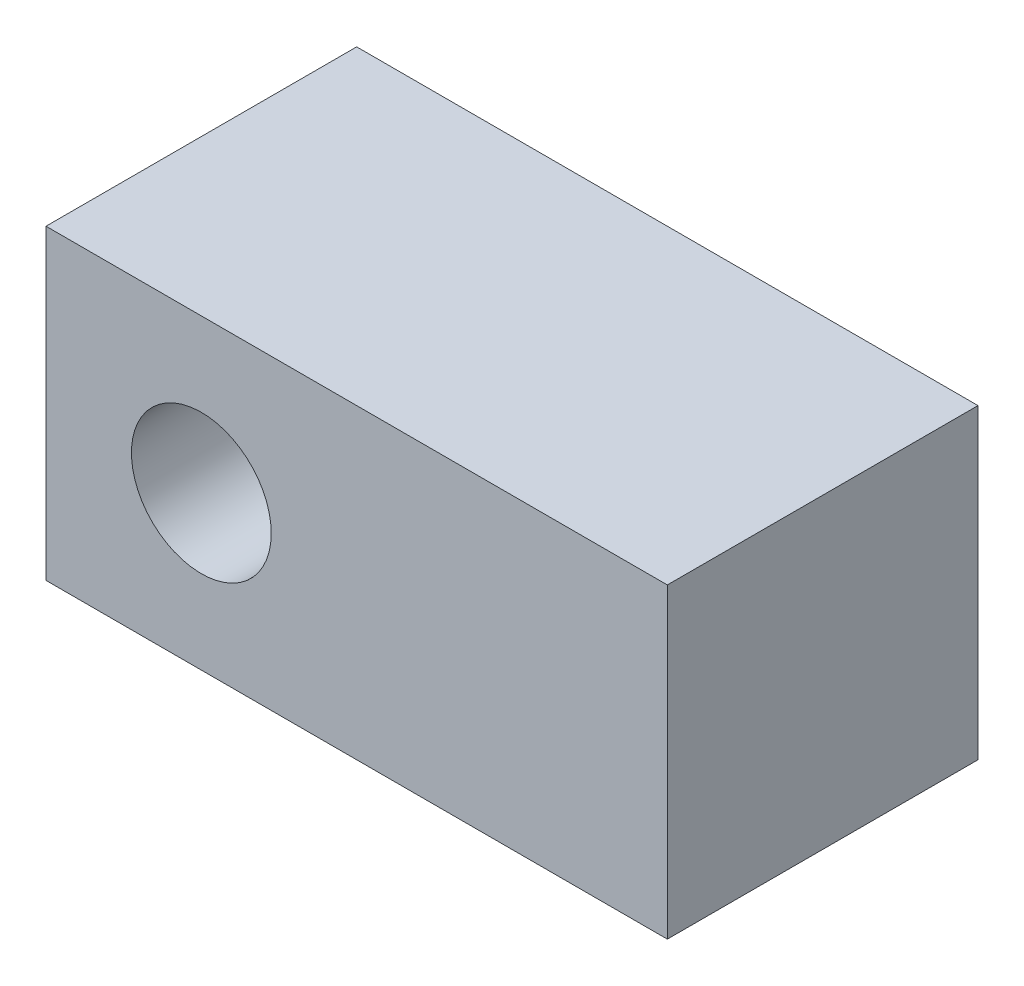
SolidWorks part; units mm, degrees
ref_plane "Front Plane" through (0, 0, 0) normal (0, 0, 1) x (1, 0, 0)
ref_plane "Top Plane" through (0, 0, 0) normal (0, 1, 0) x (1, 0, 0)
ref_plane "Right Plane" through (0, 0, 0) normal (1, 0, 0) x (0, 0, -1)
sketch "Sketch1" plane through (0, 0, 0) normal (0, 0, 1) x (1, 0, 0)
  line L0 (20, 48.4432) -> (20, -8.9455) construction
  line L1 (0, 0) -> (40, 0)
  line L2 (0, 0) -> (0, 19.7489)
  line L3 (0, 19.7489) -> (40, 19.7489)
  line L4 (40, 0) -> (40, 19.7489)
  line L5 (-10.3615, 9.8744) -> (10.3615, 9.8744) construction
  circle A1 centre (10, 9.8744) radius 4.5
  point P8 (20, 19.7489)
  point P11 (0, 9.8744)
  point P15 (0, 0)
  point P16 (-18.5983, 6.2022)
  point P17 (-10.3615, 9.8744)
  dimension "D2" = 10
  dimension "D1" = 10
extrude "Boss-Extrude1" add sketch "Sketch1" along normal blind 20
